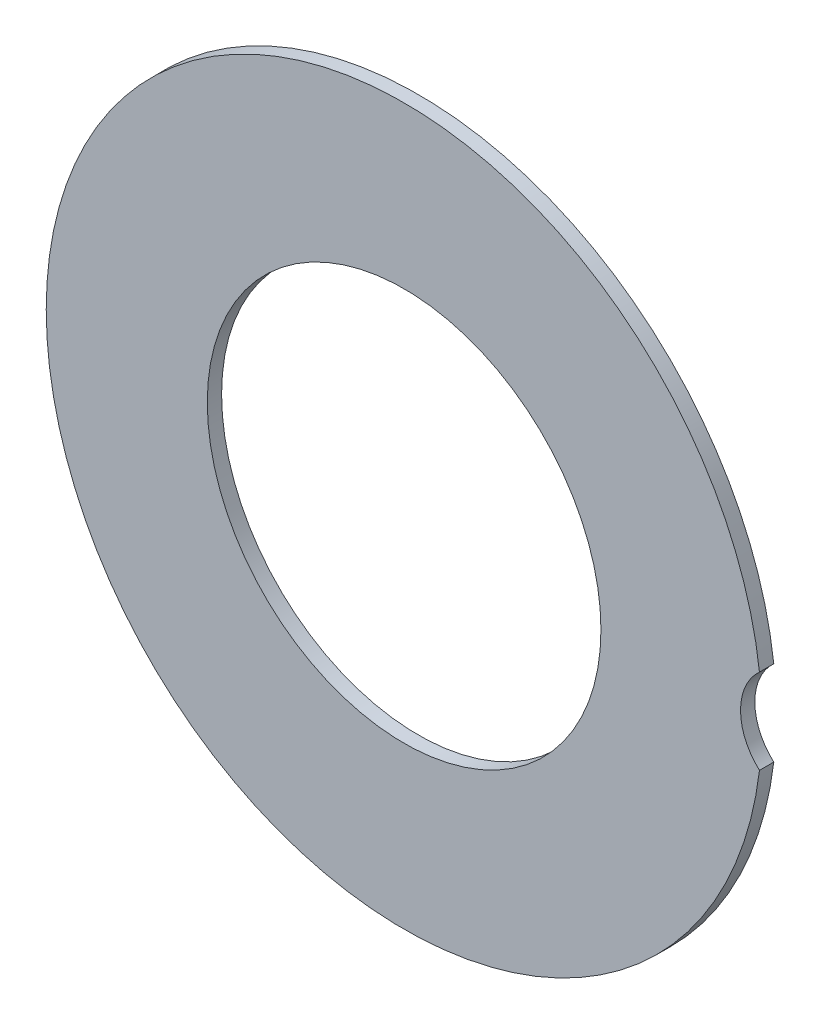
SolidWorks part; units mm, degrees
ref_plane "Front Plane" through (0, 0, 0) normal (0, 0, 1) x (1, 0, 0)
ref_plane "Top Plane" through (0, 0, 0) normal (0, 1, 0) x (1, 0, 0)
ref_plane "Right Plane" through (0, 0, 0) normal (1, 0, 0) x (0, 0, -1)
sketch "Sketch1" plane through (0, 0, 0) normal (0, 0, 1) x (1, 0, 0)
  circle A0 centre (0, 0) radius 100
  circle A1 centre (0, 0) radius 55
extrude "Boss-Extrude1" add sketch "Sketch1" along normal blind 4
sketch "Sketch2" plane through (0, 0, 0) normal (0, 0, 1) x (1, 0, 0)
  circle A0 centre (110, 0) radius 16
extrude "Cut-Extrude2" cut sketch "Sketch2" along normal blind 5
